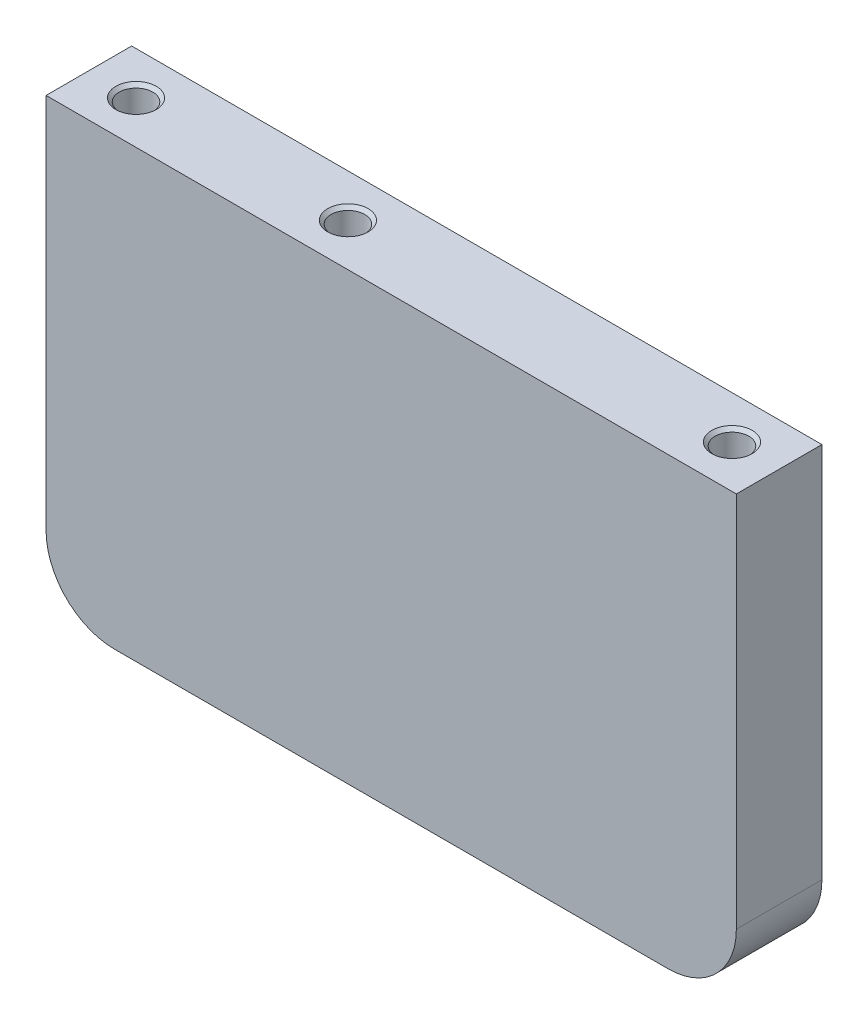
SolidWorks part; units mm, degrees
ref_plane "Front Plane" through (0, 0, 0) normal (0, 0, 1) x (1, 0, 0)
ref_plane "Top Plane" through (0, 0, 0) normal (0, 1, 0) x (1, 0, 0)
ref_plane "Right Plane" through (0, 0, 0) normal (1, 0, 0) x (0, 0, -1)
sketch "Sketch1" plane through (0, 0, 0) normal (0, 0, 1) x (1, 0, 0)
  line L10 (-33.225, 19.05) -> (18, 19.05)
  line L11 (-33.225, 19.05) -> (-33.225, -14)
  line L12 (-33.225, -14) -> (18, -14)
  line L13 (18, 19.05) -> (18, -14)
  circle A2 centre (0, 0) radius 11.05 construction
  circle A3 centre (-22.225, 0) radius 3.35 construction
  dimension "D2" = 6.7
  dimension "D5" = 19.05
  dimension "D6" = 11
  dimension "D3" = 22.225
  dimension "D1" = 22.1
  dimension "D8" = 51.225
  dimension "D4" = 14
  dimension "D7" = 18
extrude "Boss-Extrude1" add sketch "Sketch1" against normal blind 6.35
sketch "Sketch8" plane through (0, 19.05, 0) normal (0, 1, 0) x (1, 0, 0)
  line L0 (-33.225, 3.175) -> (18, 3.175) construction
  line L1 (-33.225, 6.35) -> (-33.225, 0) construction
  line L2 (18, 6.35) -> (18, 0) construction
  circle A1 centre (-29.725, 3.175) radius 1.25
  circle A2 centre (-14, 3.175) radius 1.25
  circle A3 centre (14.5, 3.175) radius 1.25
  dimension "D1" = 2.5
  dimension "D2" = 3.5
  dimension "D3" = 3.5
  dimension "D4" = 14
extrude "Cut-Extrude4" cut sketch "Sketch8" against normal blind 15
fillet "Fillet3" radius 5.08 2 edges at (18, -14, -3.175) (-33.225, -14, -3.175)
sketch "Sketch10" plane through (0, 0, -6.35) normal (0, 0, -1) x (-1, 0, 0)
  circle A0 centre (22.225, 0) radius 3.35 construction
  circle A1 centre (0, 0) radius 11.05 construction
  circle A2 centre (22.225, 0) radius 3.35
  circle A3 centre (0, 0) radius 11.05
extrude "Cut-Extrude5" cut sketch "Sketch10" against normal offset from surface (4.7625 mm away) 1.5875 up to face at (-7.6125, -1.6407, 0)
chamfer "Chamfer1" distance 0.25 angle 45 3 edges at (14.5, 19.05, -1.925) (-14, 19.05, -1.925) (-29.725, 19.05, -1.925)
